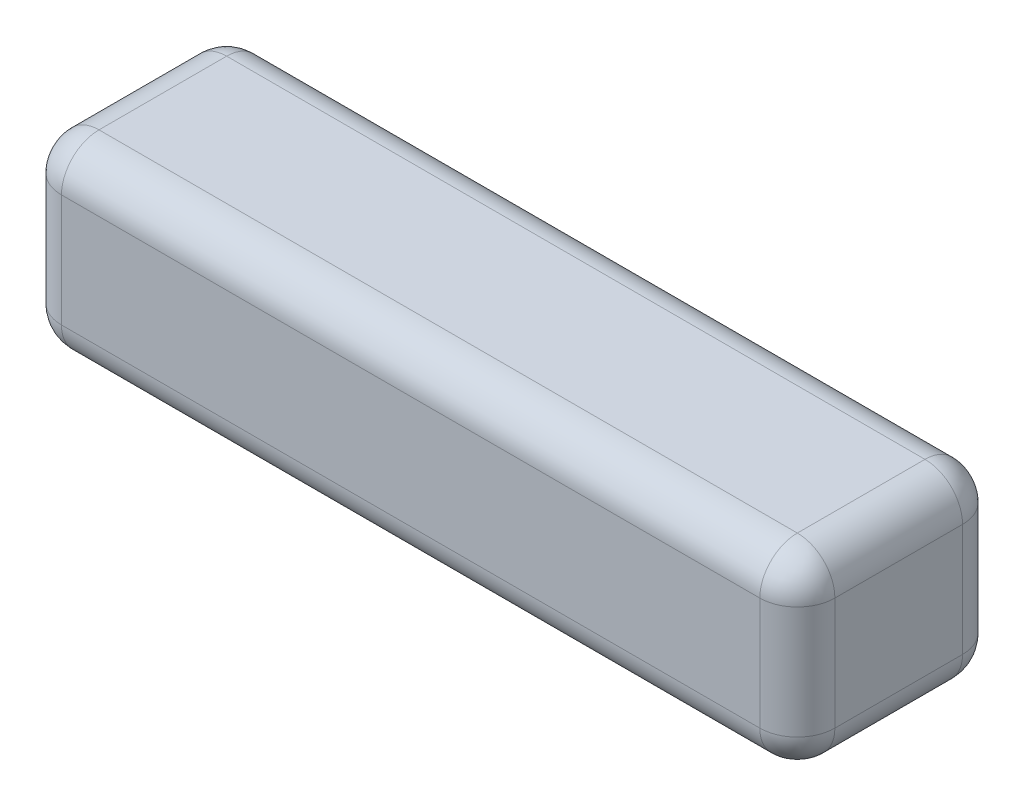
SolidWorks part; units mm, degrees
ref_plane "Front Plane" through (0, 0, 0) normal (0, 0, 1) x (1, 0, 0)
ref_plane "Top Plane" through (0, 0, 0) normal (0, 1, 0) x (1, 0, 0)
ref_plane "Right Plane" through (0, 0, 0) normal (1, 0, 0) x (0, 0, -1)
sketch "Sketch1" plane through (0, 0, 0) normal (0, 1, 0) x (1, 0, 0)
  line L1 (-51.5, 13.5) -> (51.5, 13.5)
  line L2 (-51.5, 13.5) -> (-51.5, -13.5)
  line L3 (-51.5, -13.5) -> (51.5, -13.5)
  line L4 (51.5, 13.5) -> (51.5, -13.5)
  line L5 (-51.5, 13.5) -> (51.5, -13.5) construction
  line L6 (-51.5, -13.5) -> (51.5, 13.5) construction
  point P0 (0, 0)
  dimension "D1" = 27
  dimension "D2" = 103
extrude "Boss-Extrude1" add sketch "Sketch1" along normal blind 25
fillet "Fillet1" radius 5 12 edges at (51.5, 12.5, 13.5) (-51.5, 12.5, 13.5) (-51.5, 0, 0) (0, 0, 13.5) (51.5, 0, 0) (51.5, 12.5, -13.5) (-51.5, 12.5, -13.5) (0, 0, -13.5) (0, 25, 13.5) (-51.5, 25, 0) (0, 25, -13.5) (51.5, 25, 0)
